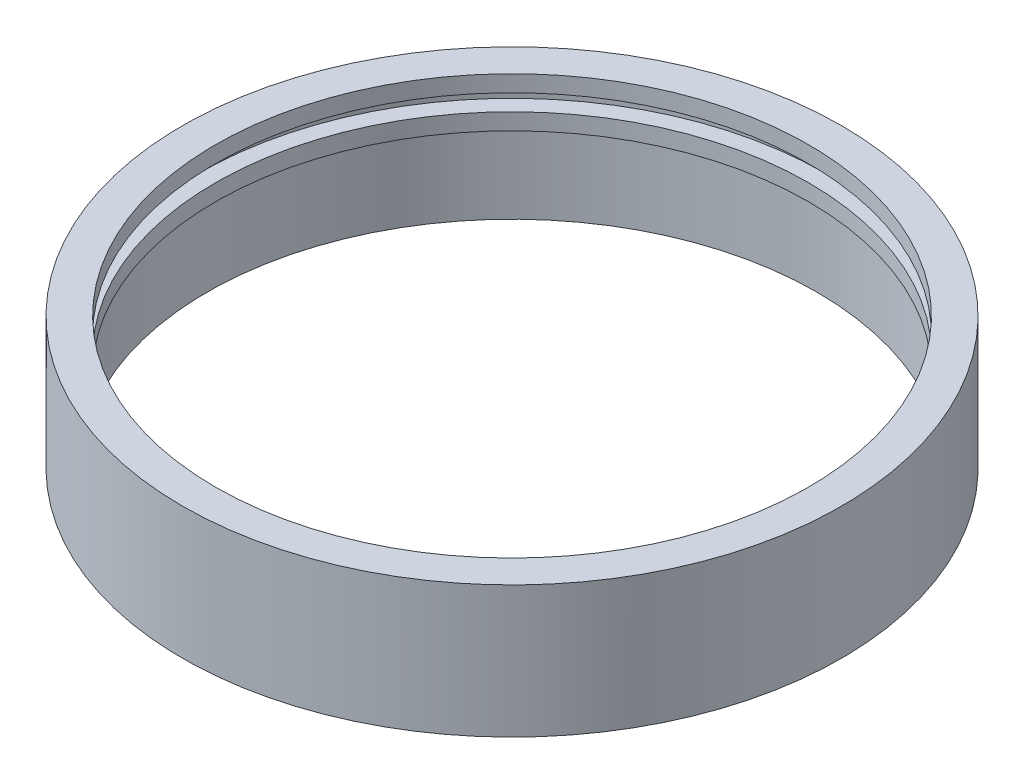
SolidWorks part; units mm, degrees
ref_plane "Front Plane" through (0, 0, 0) normal (0, 0, 1) x (1, 0, 0)
ref_plane "Top Plane" through (0, 0, 0) normal (0, 1, 0) x (1, 0, 0)
ref_plane "Right Plane" through (0, 0, 0) normal (1, 0, 0) x (0, 0, -1)
sketch "Sketch1" plane through (0, 0, 0) normal (0, 1, 0) x (1, 0, 0)
  circle A0 centre (0, 0) radius 20
  circle A1 centre (0, 0) radius 18
  dimension "D1" = 40
  dimension "D2" = 36
extrude "Boss-Extrude1" add sketch "Sketch1" along normal blind 1
sketch "Sketch2" plane through (0, 0, 0) normal (0, -1, 0) x (1, 0, 0)
  circle A0 centre (0, 0) radius 19
  circle A1 centre (0, 0) radius 20
  circle A2 centre (0, 0) radius 20 construction
  dimension "D1" = 38
  dimension "D2" = 0
extrude "Boss-Extrude2" add sketch "Sketch2" along normal blind 1
sketch "Sketch3" plane through (0, -1, 0) normal (0, -1, 0) x (1, 0, 0)
  circle A0 centre (0, 0) radius 18
  circle A1 centre (0, 0) radius 20
  circle A2 centre (0, 0) radius 18 construction
  circle A3 centre (0, 0) radius 20 construction
  dimension "D1" = 0
  dimension "D2" = 0
extrude "Boss-Extrude3" add sketch "Sketch3" along normal blind 1
sketch "Sketch4" plane through (0, -2, 0) normal (0, -1, 0) x (1, 0, 0)
  circle A0 centre (0, 0) radius 18.5
  circle A1 centre (0, 0) radius 20
  circle A2 centre (0, 0) radius 20 construction
  dimension "D1" = 0
  dimension "D2" = 37
extrude "Boss-Extrude4" add sketch "Sketch4" along normal blind 5
